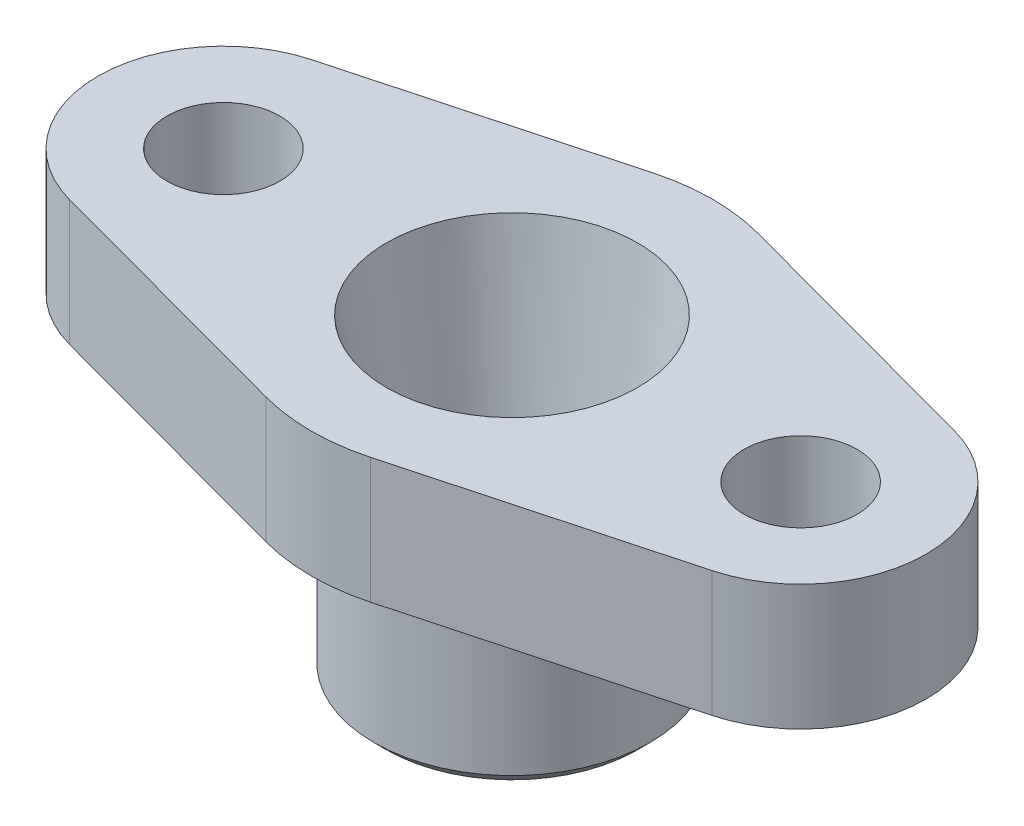
SolidWorks part; units mm, degrees
ref_plane "Front" through (0, 0, 0) normal (0, 0, 1) x (1, 0, 0)
ref_plane "Top" through (0, 0, 0) normal (0, 1, 0) x (1, 0, 0)
ref_plane "Right" through (0, 0, 0) normal (1, 0, 0) x (0, 0, -1)
sketch "Эскиз1" plane through (0, 0, 0) normal (0, 1, 0) x (1, 0, 0)
  line L0 (0, 22.695) -> (0, -24.3277) construction
  line L1 (-47.0197, 0) -> (43.1098, 0) construction
  line L2 (-25.6087, 9.6537) -> (-4.1739, 15.446)
  line L3 (-25.6087, -9.6537) -> (-4.1739, -15.446)
  line L4 (25.6087, -9.6537) -> (4.1739, -15.446)
  line L5 (25.6087, 9.6537) -> (4.1739, 15.446)
  arc A0 (4.1739, 15.446) -> (-4.1739, 15.446) centre (0, 0) ccw
  arc A1 (-25.6087, 9.6537) -> (-25.6087, -9.6537) centre (-23, 0) ccw
  arc A2 (-4.1739, -15.446) -> (4.1739, -15.446) centre (0, 0) ccw
  circle A3 centre (-23, 0) radius 4.5
  circle A4 centre (23, 0) radius 4.5
  arc A5 (25.6087, 9.6537) -> (25.6087, -9.6537) centre (23, 0) cw
  dimension "D1" = 32
  dimension "D2" = 10
  dimension "D3" = 9
  dimension "D4" = 46
extrude "Бобышка-Вытянуть1" add sketch "Эскиз1" against normal blind 10
sketch "Эскиз2" plane through (0, 0, 0) normal (0, 1, 0) x (1, 0, 0)
  circle A0 centre (0, 0) radius 11
  dimension "D1" = 22
extrude "Бобышка-Вытянуть2" add sketch "Эскиз2" against normal blind 25
sketch "Эскиз3" plane through (0, 0, 0) normal (0, 0, 1) x (1, 0, 0)
  line L0 (0, 4.0063) -> (0, -29.6189) construction
  line L1 (4.1739, 0) -> (-4.1739, 0) construction
  line L2 (0, 0) -> (-10, 0)
  line L3 (-25.6087, 0) -> (-4.1739, 0) construction
  line L4 (-10, 0) -> (-8.1227, -13.1414)
  line L5 (-7.1327, -14) -> (-6, -14)
  line L6 (-6, -14) -> (-6, -25)
  line L7 (-11, -25) -> (11, -25) construction
  line L8 (-6, -25) -> (0, -25)
  line L9 (0, -25) -> (0, 0)
  arc A0 (-8.1227, -13.1414) -> (-7.1327, -14) centre (-7.1327, -13) ccw
  point P17 (-8, -14)
  dimension "D5" = 1
  dimension "D1" = 20
  dimension "D2" = 16
  dimension "D3" = 12
  dimension "D4" = 14
revolve "Вырез-Повернуть1" cut sketch "Эскиз3" angle 360 about L0
fillet "Скругление1" radius 2 1 edges at (0, -10, -11)
chamfer "Фаска1" distance 1 angle 45 1 edges at (0, -25, 11)
